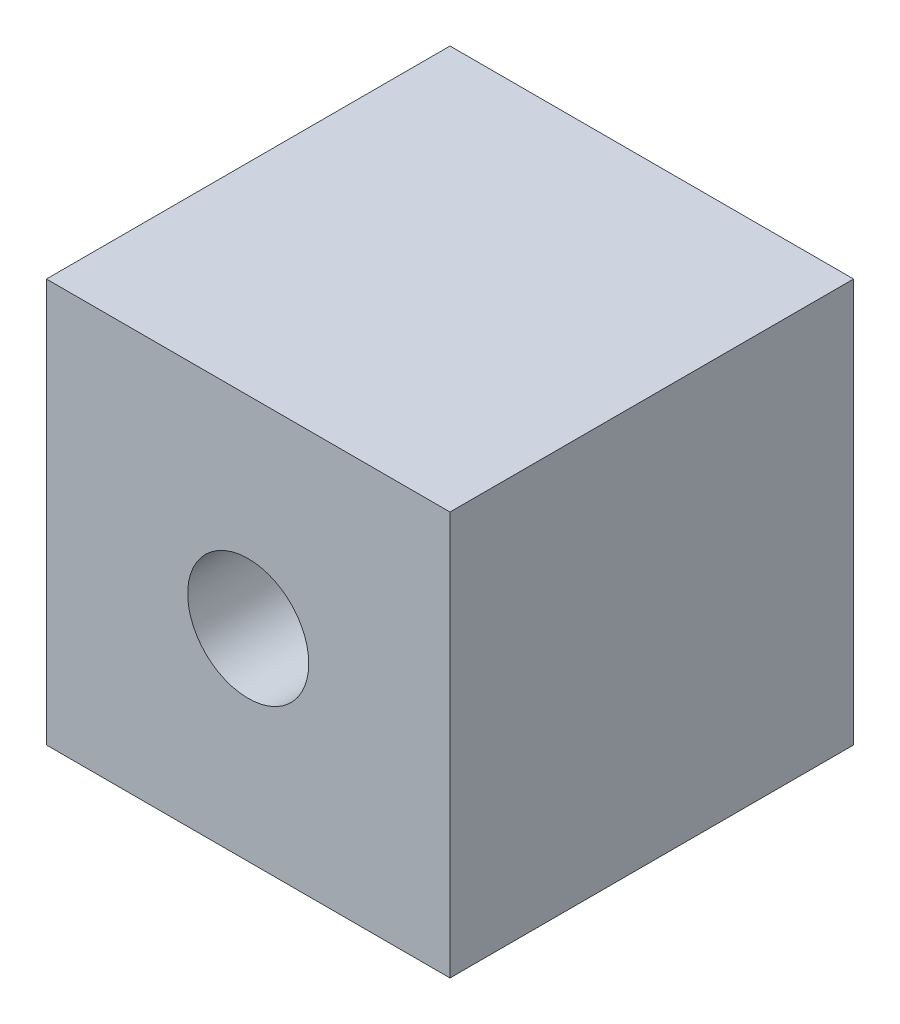
SolidWorks part; units mm, degrees
ref_plane "Front Plane" through (0, 0, 0) normal (0, 0, 1) x (1, 0, 0)
ref_plane "Top Plane" through (0, 0, 0) normal (0, 1, 0) x (1, 0, 0)
ref_plane "Right Plane" through (0, 0, 0) normal (1, 0, 0) x (0, 0, -1)
sketch "Sketch1" plane through (0, 0, 0) normal (0, 0, 1) x (1, 0, 0)
  line L1 (0, 0) -> (10, 0)
  line L2 (0, 0) -> (0, 10)
  line L3 (0, 10) -> (10, 10)
  line L4 (10, 0) -> (10, 10)
extrude "Boss-Extrude1" add sketch "Sketch1" along normal blind 10
sketch "Sketch2" plane through (0, 0, 0) normal (0, 0, 1) x (1, 0, 0)
  circle A0 centre (5, 5) radius 1.5
extrude "Cut-Extrude2" cut sketch "Sketch2" along normal through all
